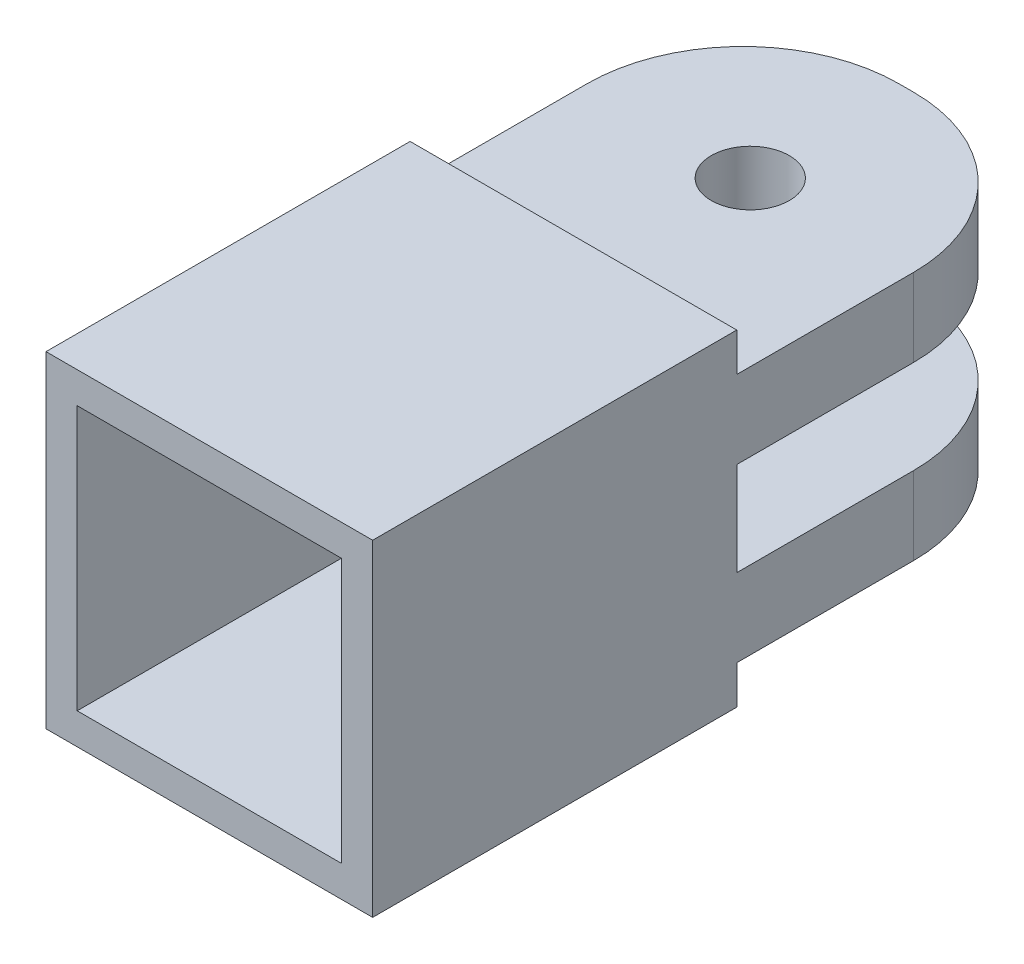
SolidWorks part; units mm, degrees
ref_plane "Front Plane" through (0, 0, 0) normal (0, 0, 1) x (1, 0, 0)
ref_plane "Top Plane" through (0, 0, 0) normal (0, 1, 0) x (1, 0, 0)
ref_plane "Right Plane" through (0, 0, 0) normal (1, 0, 0) x (0, 0, -1)
sketch "Sketch1" plane through (0, 0, 0) normal (0, 0, 1) x (1, 0, 0)
  line L0 (0, 34.2563) -> (0, -38.0151) construction
  line L1 (-50.9145, 0) -> (58.9447, 0) construction
  line L2 (-12.7, 12.7) -> (-12.7, -12.7)
  line L3 (-15.7, 15.7) -> (15.7, 15.7)
  line L4 (-15.7, 15.7) -> (-15.7, -15.7)
  line L5 (-15.7, -15.7) -> (15.7, -15.7)
  line L6 (15.7, 15.7) -> (15.7, -15.7)
  line L7 (-12.7, -12.7) -> (12.7, -12.7)
  line L8 (12.7, 12.7) -> (12.7, -12.7)
  line L9 (-12.7, 12.7) -> (12.7, 12.7)
  dimension "D1" = 15.7
  dimension "D2" = 15.7
  dimension "D3" = 15.7
  dimension "D4" = 15.7
  dimension "D5" = 3
extrude "Boss-Extrude1" add sketch "Sketch1" along normal blind 30
sketch "Sketch2" plane through (0, 0, 0) normal (0, 0, -1) x (-1, 0, 0)
  line L0 (15.7, 15.7) -> (15.7, -15.7)
  line L1 (15.7, -15.7) -> (-15.7, -15.7)
  line L2 (-15.7, -15.7) -> (-15.7, 15.7)
  line L3 (-15.7, 15.7) -> (15.7, 15.7)
extrude "Boss-Extrude2" add sketch "Sketch2" along normal blind 5
sketch "Sketch3" plane through (0, 0, -5) normal (0, 0, -1) x (-1, 0, 0)
  line L6 (-15.7, 12) -> (15.7, 12)
  line L7 (-15.7, 15.7) -> (-15.7, -15.7) construction
  line L8 (15.7, -15.7) -> (15.7, 15.7) construction
  line L9 (15.7, 12) -> (15.7, 4.5)
  line L10 (15.7, 4.5) -> (-15.7, 4.5)
  line L11 (-15.7, 4.5) -> (-15.7, 12)
  dimension "D1" = 7.5
  dimension "D2" = 4.5
extrude "Boss-Extrude3" add sketch "Sketch3" along normal blind 5
sketch "Sketch6" plane through (0, 12, 0) normal (0, 1, 0) x (1, 0, 0)
  line L0 (-15.7, 10) -> (-15.7, 22)
  line L1 (0.7, 37) -> (-0.7, 37)
  line L2 (15.7, 22) -> (15.7, 10)
  line L3 (15.7, 10) -> (-15.7, 10)
  arc A0 (-15.7, 22) -> (-0.7, 37) centre (-0.7, 22) cw
  arc A1 (0.7, 37) -> (15.7, 22) centre (0.7, 22) cw
  circle A2 centre (0, 22) radius 3.75
  point P10 (15.7, 37)
  dimension "D2" = 15
  dimension "D3" = 15
  dimension "D1" = 27
extrude "Boss-Extrude6" add sketch "Sketch6" against normal blind 7.5
mirror "Mirror1" about plane through (0, 0, 0) normal (0, 1, 0) of "Boss-Extrude6", "Boss-Extrude3"
